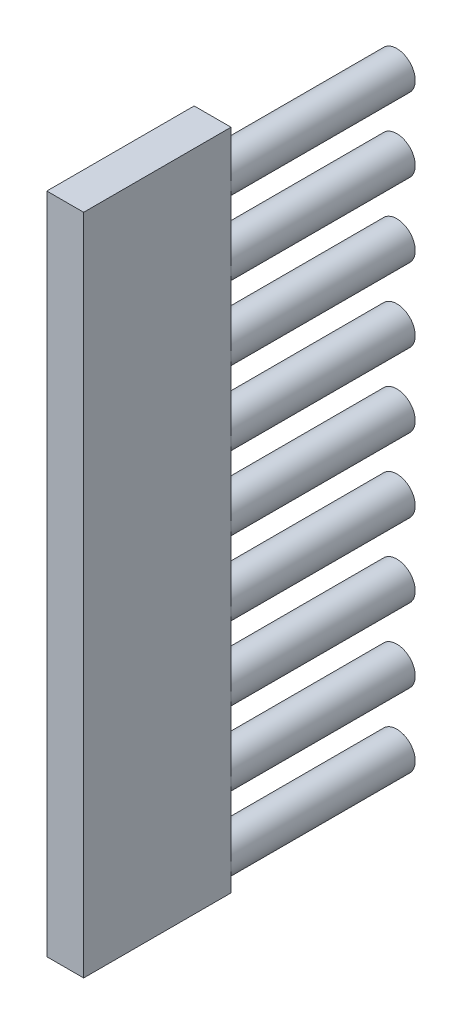
SolidWorks part; units mm, degrees
ref_plane "Front Plane" through (0, 0, 0) normal (1, 0, 0) x (0, 1, 0)
ref_plane "Top Plane" through (0, 0, 0) normal (0, 0, 1) x (0, 1, 0)
ref_plane "Right Plane" through (0, 0, 0) normal (0, 1, 0) x (-1, 0, 0)
sketch "Sketch1" plane through (0, 0, 0) normal (1, 0, 0) x (0, 1, 0)
  line L1 (0, 0) -> (90, 0)
  line L2 (0, 0) -> (0, 20)
  line L3 (0, 20) -> (90, 20)
  line L4 (90, 0) -> (90, 20)
  dimension "D1" = 90
  dimension "D2" = 20
extrude "Boss-Extrude1" add sketch "Sketch1" along normal blind 5
sketch "Sketch2" plane through (0, 0, 0) normal (0, 0, -1) x (1, 0, 0)
  line L0 (2.5, 0) -> (2.5, -3) construction
  line L1 (5, 0) -> (0, 0) construction
  circle A0 centre (2.5, -3) radius 2.5
  circle A1 centre (2.5, -13) radius 2.5
  circle A2 centre (2.5, -23) radius 2.5
  circle A3 centre (2.5, -33) radius 2.5
  circle A4 centre (2.5, -43) radius 2.5
  circle A5 centre (2.5, -53) radius 2.5
  circle A6 centre (2.5, -63) radius 2.5
  circle A7 centre (2.5, -73) radius 2.5
  circle A8 centre (2.5, -83) radius 2.5
  dimension "D1" = 3
  dimension "D2" = 9
extrude "Boss-Extrude2" add sketch "Sketch2" along normal blind 25
